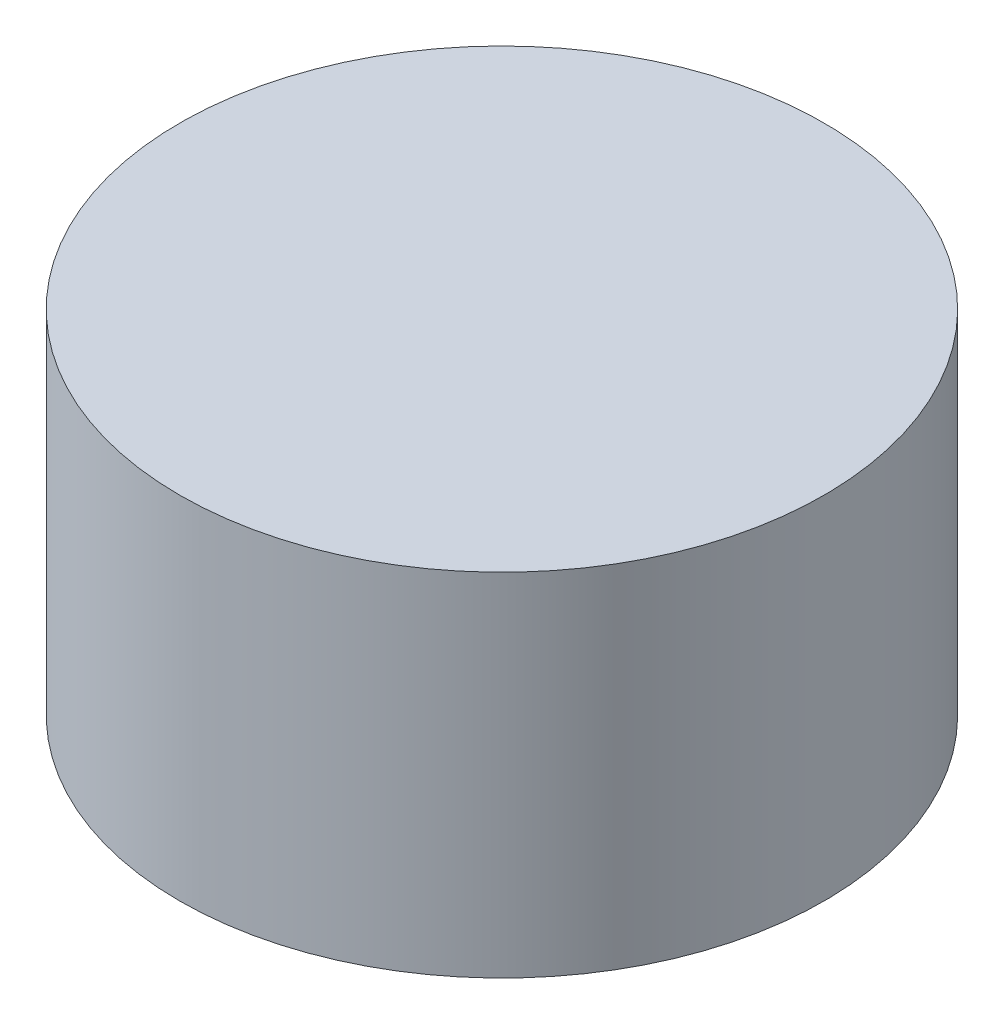
SolidWorks part; units mm, degrees
ref_plane "Front Plane" through (0, 0, 0) normal (0, 0, 1) x (1, 0, 0)
ref_plane "Top Plane" through (0, 0, 0) normal (0, 1, 0) x (1, 0, 0)
ref_plane "Right Plane" through (0, 0, 0) normal (1, 0, 0) x (0, 0, -1)
sketch "Sketch1" plane through (0, 0, 0) normal (0, 1, 0) x (1, 0, 0)
  circle A0 centre (0, 0) radius 73.35
  dimension "D1" = 146.7
extrude "Boss-Extrude1" add sketch "Sketch1" along normal mid plane 80
